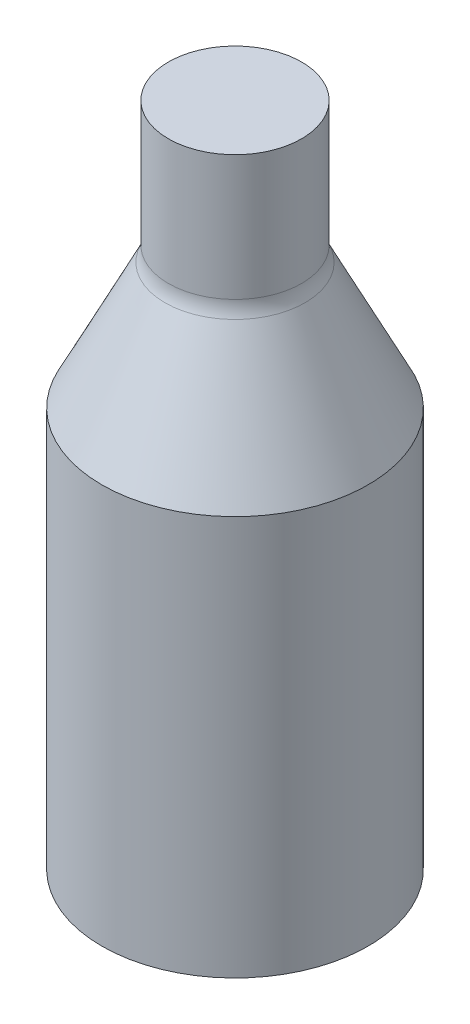
SolidWorks part; units mm, degrees
ref_plane "Front Plane" through (0, 0, 0) normal (0, 0, 1) x (1, 0, 0)
ref_plane "Top Plane" through (0, 0, 0) normal (0, 1, 0) x (1, 0, 0)
ref_plane "Right Plane" through (0, 0, 0) normal (1, 0, 0) x (0, 0, -1)
other "Configuration Table"
sketch "Sketch1" plane through (0, 0, 0) normal (0, 0, 1) x (1, 0, 0)
  line L0 (0, 0) -> (0, 100)
  line L1 (0, 100) -> (10, 100)
  line L2 (10, 100) -> (10, 81.1803)
  line L3 (10.5279, 78.9443) -> (20, 60)
  line L4 (20, 60) -> (20, 0)
  line L5 (20, 0) -> (0, 0)
  line L6 (0, 109.5719) -> (0, -10) construction
  arc A0 (10, 81.1803) -> (10.5279, 78.9443) centre (15, 81.1803) ccw
  point P9 (10, 80)
  dimension "D1" = 100
  dimension "D4" = 5
  dimension "D2" = 20
  dimension "D3" = 60
revolve "Revolve1" add sketch "Sketch1" angle 360 about L6
